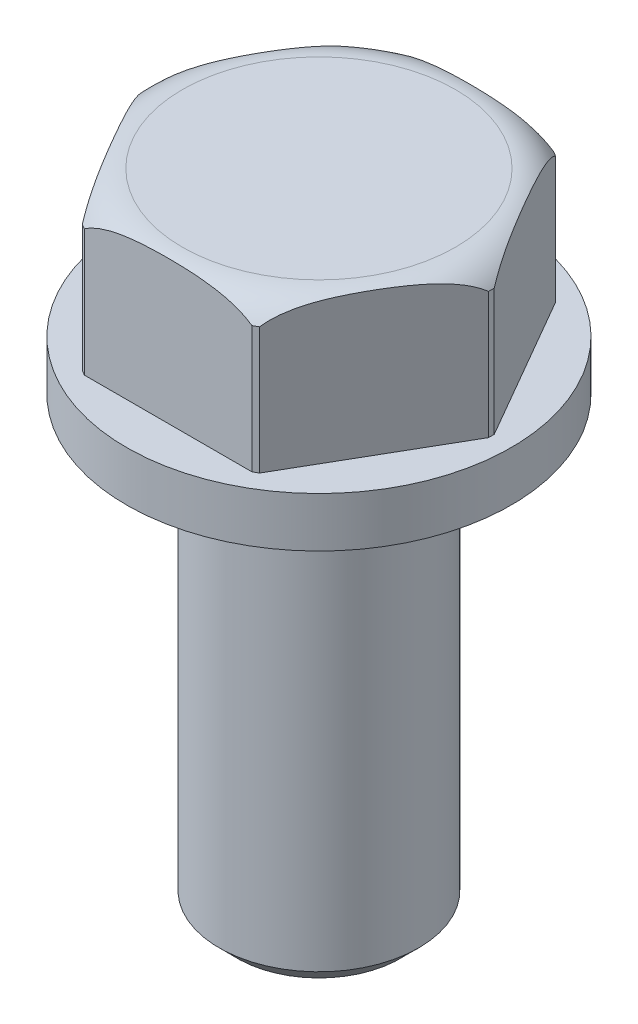
SolidWorks part; units mm, degrees
ref_plane "Front Plane" through (0, 0, 0) normal (0, 0, 1) x (1, 0, 0)
ref_plane "Top Plane" through (0, 0, 0) normal (0, 1, 0) x (1, 0, 0)
ref_plane "Right Plane" through (0, 0, 0) normal (1, 0, 0) x (0, 0, -1)
sketch "Sketch1" plane through (0, 0, 0) normal (0, 0, 1) x (1, 0, 0)
  line L0 (0, 0) -> (6.35, 0)
  line L1 (6.35, 0) -> (6.35, 28.5496)
  line L2 (6.35, 28.5496) -> (12.2555, 28.5496)
  line L3 (12.2555, 28.5496) -> (12.2555, 31.7246)
  line L4 (12.2555, 31.7246) -> (10.9855, 31.7246)
  line L5 (10.9855, 31.7246) -> (10.9855, 40.9956)
  line L6 (10.9855, 40.9956) -> (0, 40.9956)
  line L7 (0, 40.9956) -> (0, 0) construction
  line L8 (0, 0) -> (0, 40.9956)
  dimension "D1" = 12.7
  dimension "D2" = 21.971
  dimension "D3" = 24.511
  dimension "D4" = 40.9956
  dimension "D5" = 9.271
  dimension "D6" = 3.175
revolve "Revolve1" add sketch "Sketch1" angle 360 about L7
sketch "Sketch3" plane through (0, 40.9956, 0) normal (0, 1, 0) x (1, 0, 0)
  line L1 (-5.334, 9.6036) -> (5.334, 9.6036)
  line L2 (-5.334, 9.6036) -> (-5.334, 15.0011)
  line L3 (-5.334, 15.0011) -> (5.334, 15.0011)
  line L4 (5.334, 9.6036) -> (5.334, 15.0011)
  line L5 (-5.334, 9.6036) -> (5.334, 15.0011) construction
  line L6 (-5.334, 15.0011) -> (5.334, 9.6036) construction
  circle A0 centre (0, 0) radius 10.9855 construction
  circle A1 centre (0, 0) radius 10.9855 construction
  point P4 (0, 12.3023)
  point P7 (0, 0)
  point P10 (0, 0)
  dimension "D1" = 10.668
extrude "Cut-Extrude1" cut sketch "Sketch3" against normal up to surface (9.271 mm away) up to face at (-10.9855, 31.7246, 0)
pattern_circular "CirPattern1" count 6 over 360 about axis through (0, 0, 0) along (0, 1, 0) of "Cut-Extrude1"
sketch "Sketch4" plane through (0, 0, 0) normal (0, 0, 1) x (1, 0, 0)
  line L0 (11.176, 39.4716) -> (11.176, 40.9956)
  line L1 (11.176, 40.9956) -> (8.6995, 40.9956)
  line L2 (10.984, 40.9956) -> (5.65, 40.9956) construction
  line L3 (0, 28.5496) -> (0, 47.0465) construction
  line L4 (-6.35, 28.5496) -> (6.35, 28.5496) construction
  arc A1 (11.176, 39.4716) -> (8.6995, 40.9956) centre (8.6995, 38.2214) ccw
  dimension "D1" = 22.352
  dimension "D2" = 17.399
  dimension "D3" = 1.524
revolve "Cut-Revolve1" cut sketch "Sketch4" angle 360 about L3
chamfer "Chamfer1" distance 1.1633 angle 45 1 edges at (-6.35, 0, 0)
